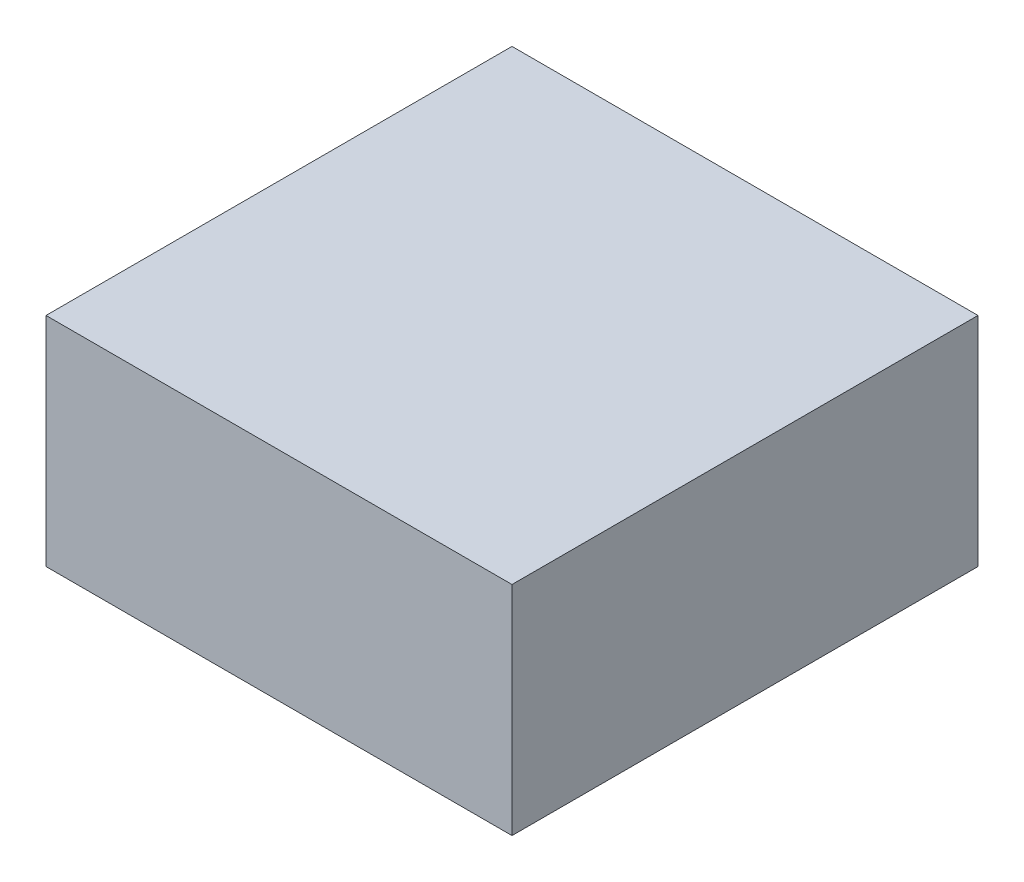
SolidWorks part; units mm, degrees
ref_plane "Front Plane" through (0, 0, 0) normal (0, 0, 1) x (1, 0, 0)
ref_plane "Top Plane" through (0, 0, 0) normal (0, 1, 0) x (1, 0, 0)
ref_plane "Right Plane" through (0, 0, 0) normal (1, 0, 0) x (0, 0, -1)
sketch "Sketch1" plane through (0, 0, 0) normal (0, 1, 0) x (1, 0, 0)
  line L1 (-75, -75) -> (75, -75)
  line L2 (-75, -75) -> (-75, 75)
  line L3 (-75, 75) -> (75, 75)
  line L4 (75, -75) -> (75, 75)
  line L5 (-75, -75) -> (75, 75) construction
  line L6 (-75, 75) -> (75, -75) construction
  point P0 (0, 0)
  dimension "D1" = 150
  dimension "D2" = 150
extrude "Boss-Extrude1" add sketch "Sketch1" along normal blind 70
